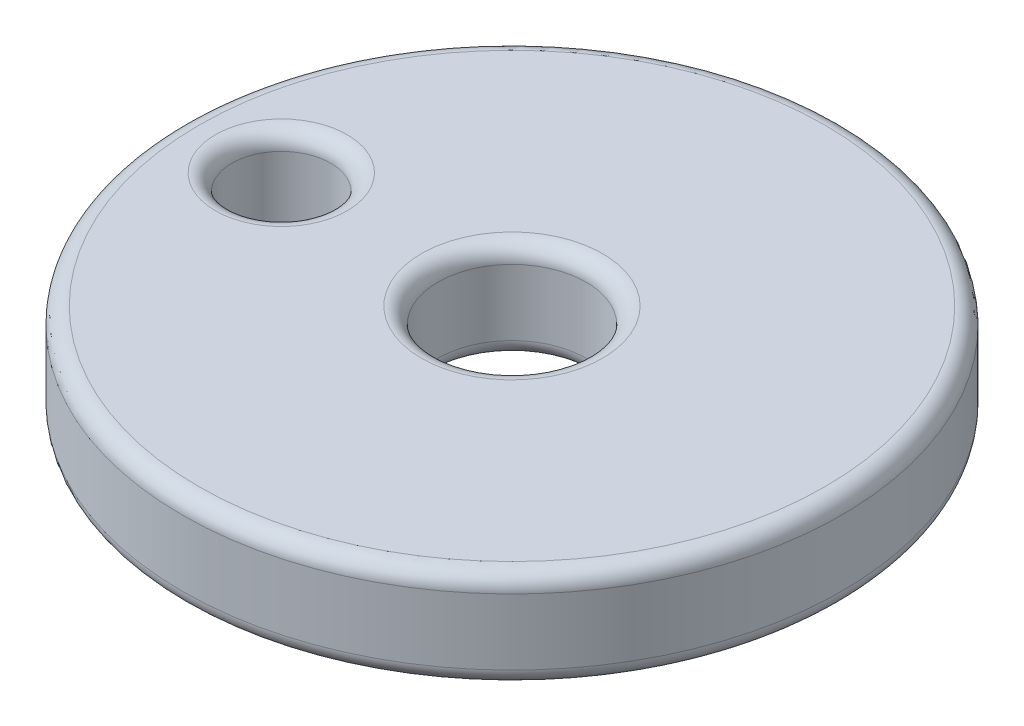
SolidWorks part; units mm, degrees
ref_plane "Front Plane" through (0, 0, 0) normal (0, 0, 1) x (1, 0, 0)
ref_plane "Top Plane" through (0, 0, 0) normal (0, 1, 0) x (1, 0, 0)
ref_plane "Right Plane" through (0, 0, 0) normal (1, 0, 0) x (0, 0, -1)
sketch "Sketch1" plane through (0, 0, 0) normal (0, 1, 0) x (1, 0, 0)
  line L1 (-10, 0) -> (-7, 0) construction
  circle A0 centre (0, 0) radius 2.25
  circle A1 centre (0, 0) radius 10
  circle A5 centre (-7, 0) radius 1.5
  dimension "D1" = 4.5
  dimension "D2" = 20
  dimension "D4" = 3
  dimension "D3" = 3
extrude "Boss-Extrude1" add sketch "Sketch1" along normal blind 3
fillet "Fillet1" radius 0.5 6 edges at (-7, 0, 1.5) (0, 0, 2.25) (0, 0, 10) (-7, 3, 1.5) (0, 3, 10) (0, 3, 2.25)
